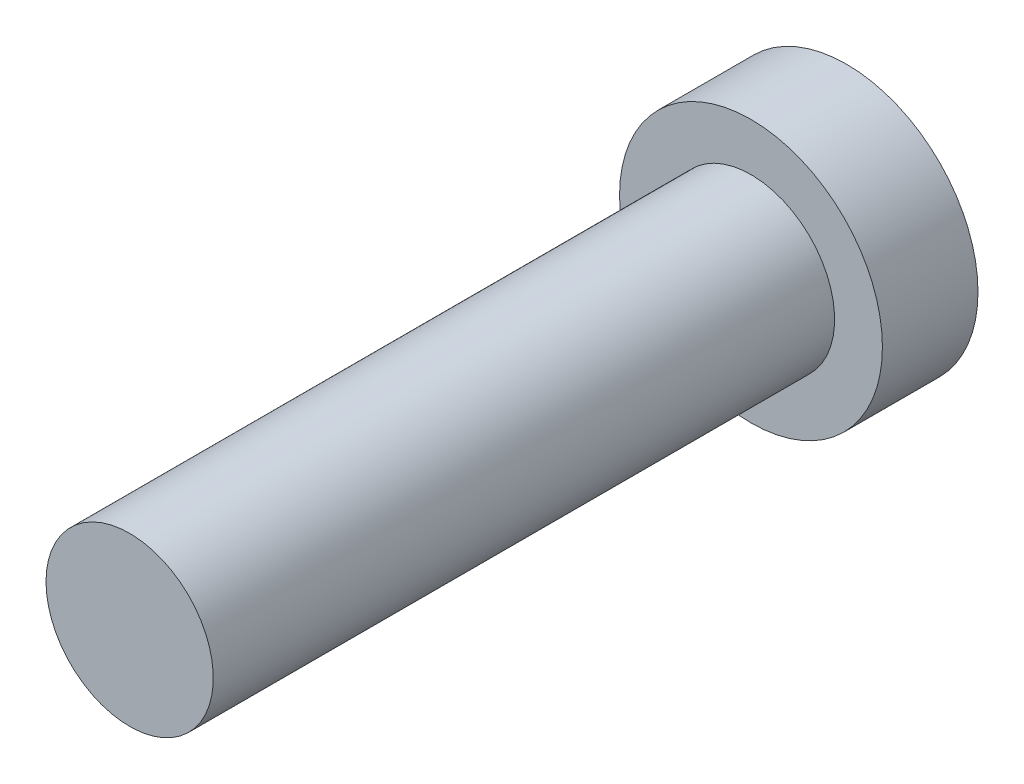
SolidWorks part; units mm, degrees
ref_plane "前基準面" through (0, 0, 0) normal (0, 0, 1) x (1, 0, 0)
ref_plane "上基準面" through (0, 0, 0) normal (0, 1, 0) x (1, 0, 0)
ref_plane "右基準面" through (0, 0, 0) normal (1, 0, 0) x (0, 0, -1)
sketch "草圖1" plane through (0, 0, 0) normal (0, 0, 1) x (1, 0, 0)
  circle A0 centre (0, 0) radius 2.75
  dimension "D1" = 5.5
extrude "伸長1" add sketch "草圖1" along normal blind 2
sketch "草圖2" plane through (0, 0, 2) normal (0, 0, 1) x (1, 0, 0)
  circle A0 centre (0, 0) radius 1.75
  dimension "D1" = 3.5
extrude "伸長2" add sketch "草圖2" along normal blind 13
